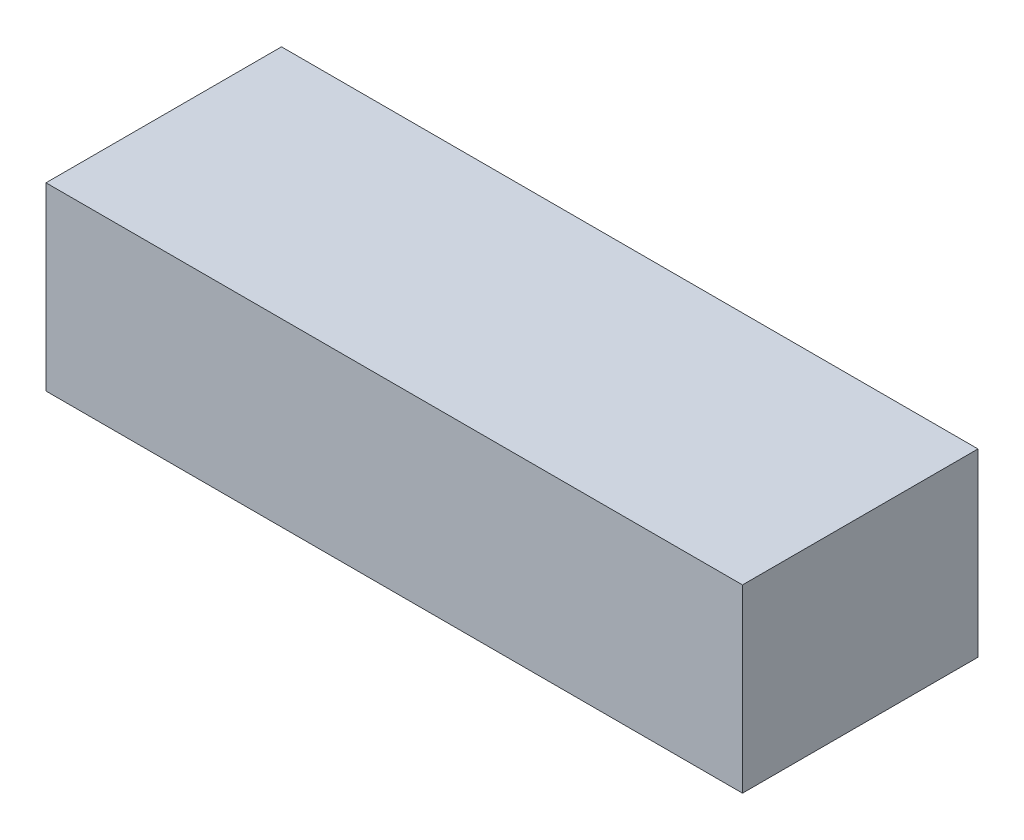
SolidWorks part; units mm, degrees
ref_plane "Front Plane" through (0, 0, 0) normal (0, 0, 1) x (1, 0, 0)
ref_plane "Top Plane" through (0, 0, 0) normal (0, 1, 0) x (1, 0, 0)
ref_plane "Right Plane" through (0, 0, 0) normal (1, 0, 0) x (0, 0, -1)
sketch "Sketch1" plane through (0, 0, 0) normal (0, 1, 0) x (1, 0, 0)
  line L1 (-69.5, -23.5) -> (69.5, -23.5)
  line L2 (-69.5, -23.5) -> (-69.5, 23.5)
  line L3 (-69.5, 23.5) -> (69.5, 23.5)
  line L4 (69.5, -23.5) -> (69.5, 23.5)
  line L5 (-69.5, -23.5) -> (69.5, 23.5) construction
  line L6 (-69.5, 23.5) -> (69.5, -23.5) construction
  point P0 (0, 0)
  dimension "D1" = 47
  dimension "D2" = 139
extrude "Boss-Extrude1" add sketch "Sketch1" along normal blind 36
sketch "Sketch2" plane through (-69.5, 0, 0) normal (-1, 0, 0) x (0, 0, 1)
  line L0 (-23.5, 36) -> (-23.5, 0) construction
  line L1 (-23.5, 23.8902) -> (-20.0587, 23.8902)
  line L2 (-23.5, 23.8902) -> (-23.5, 11.7759)
  line L3 (-23.5, 11.7759) -> (-20.0587, 11.7759)
  line L4 (-20.0587, 23.8902) -> (-20.0587, 11.7759)
  point P6 (-20.0587, 21.6716)
extrude "Cut-Extrude1" cut sketch "Sketch2" against normal blind 18
